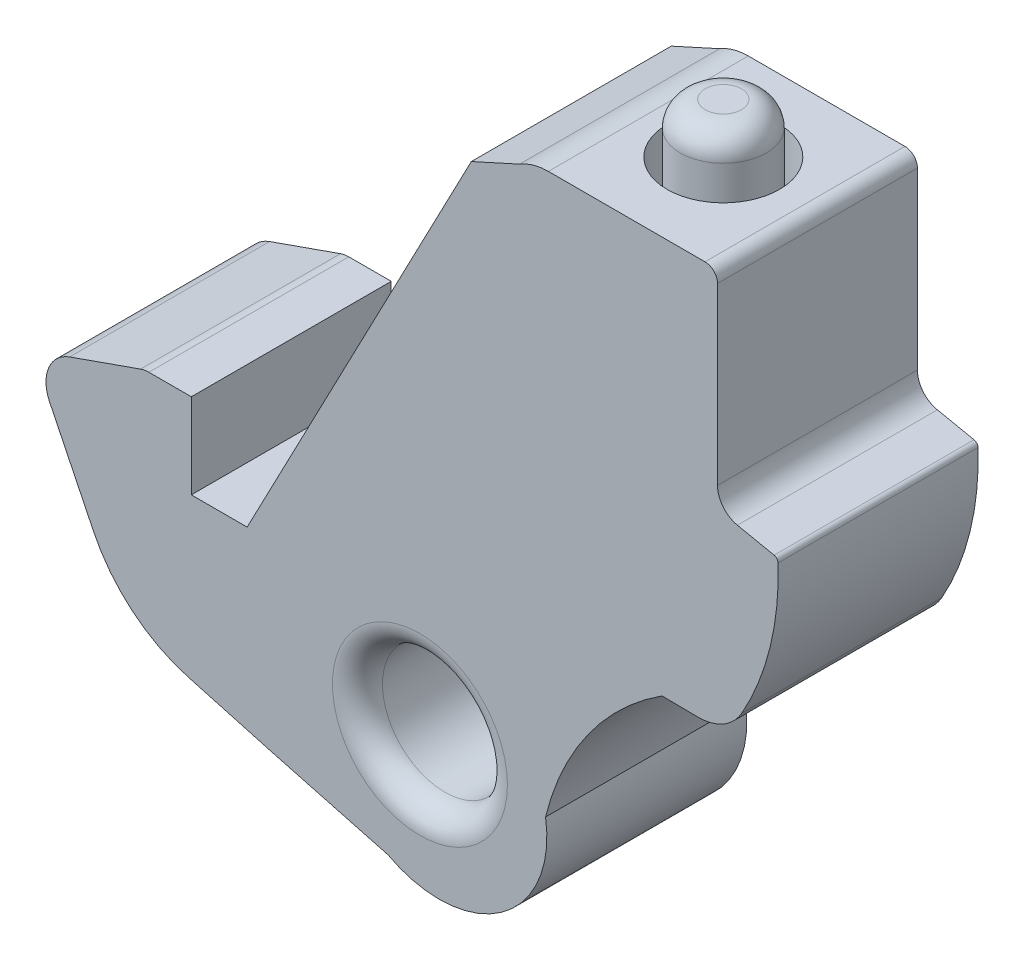
SolidWorks part; units mm, degrees
ref_plane "정면" through (0, 0, 0) normal (0, 0, 1) x (1, 0, 0)
ref_plane "윗면" through (0, 0, 0) normal (0, 1, 0) x (1, 0, 0)
ref_plane "우측면" through (0, 0, 0) normal (1, 0, 0) x (0, 0, -1)
sketch "스케치2" plane through (0, 0, 0) normal (0, 0, 1) x (1, 0, 0)
  line L0 (8.3179, 16.2244) -> (13.7243, 16.2244)
  line L1 (12.8641, 0.3222) -> (14.2933, 0.3052)
  line L4 (1.8992, -10.6672) -> (-2.7139, -9.4391)
  line L5 (-9.8819, -5.3519) -> (-11.6419, -1.7398)
  line L6 (-3.7359, -2.1289) -> (-5.9695, -2.1289)
  line L8 (13.7243, 16.2244) -> (15.0847, 16.2244)
  line L9 (-7.9998, 1.2144) -> (-10.839, 0.2157)
  line L10 (-3.7359, -2.1289) -> (5.2348, 15.0243)
  line L11 (15.0847, 16.2244) -> (15.0847, 8.7244)
  line L12 (-6.0867, -8.5069) -> (-2.7139, -9.4391)
  line L13 (-5.9695, -2.1289) -> (-5.9695, 1.2711)
  line L14 (15.8824, 7.745) -> (17.3492, 7.4421)
  line L15 (-5.9695, 1.2711) -> (-7.668, 1.2711)
  line L16 (5.2348, 15.0243) -> (7.1669, 15.9006)
  circle A0 centre (3.179, -5.8595) radius 2.5
  arc A1 (17.5086, 7.2531) -> (16.059, 1.3221) centre (6.2352, 6.8658) cw
  arc A2 (12.8641, 0.3222) -> (8.2055, -6.2043) centre (18.6948, -8.7657) ccw
  arc A3 (-9.8819, -5.3519) -> (-6.0867, -8.5069) centre (-4.4881, -2.7237) ccw
  arc A4 (16.059, 1.3221) -> (14.2933, 0.3052) centre (14.3172, 2.305) cw
  arc A5 (8.2055, -6.2043) -> (1.8992, -10.6672) centre (3.9468, -6.8736) cw
  arc A6 (-10.839, 0.2157) -> (-11.6419, -1.7398) centre (-10.3693, -1.1197) ccw
  arc A7 (17.3492, 7.4421) -> (17.5086, 7.2531) centre (17.3087, 7.2462) cw
  arc A8 (15.0847, 8.7244) -> (15.8824, 7.745) centre (16.0847, 8.7244) ccw
  arc A10 (8.3179, 16.2244) -> (7.1669, 15.9006) centre (8.3179, 14.0167) ccw
  arc A11 (-7.9998, 1.2144) -> (-7.668, 1.2711) centre (-7.668, 0.2711) cw
  dimension "D1" = 5
  dimension "D2" = 0.2
  dimension "D3" = 3.4
  dimension "D4" = 6
  dimension "D5" = 2
  dimension "D6" = 1
  dimension "D7" = 7.5
  dimension "D8" = 1
extrude "보스-돌출1" add sketch "스케치2" along normal blind 8
sketch "스케치9" plane through (0, 16.2244, 0) normal (0, 1, 0) x (1, 0, 0)
  line L1 (11.3179, -4) -> (8.3179, -4) construction
  line L2 (8.3179, -8) -> (8.3179, 0) construction
  circle A0 centre (11.3179, -4) radius 2.25
  dimension "D1" = 4.5
  dimension "D2" = 3
extrude "컷-돌출6" cut sketch "스케치9" against normal blind 2
sketch "스케치10" plane through (0, 14.2244, 0) normal (0, 1, 0) x (1, 0, 0)
  circle A0 centre (11.3179, -4) radius 1.725
  dimension "D1" = 3.45
extrude "보스-돌출3" add sketch "스케치10" along normal blind 4
fillet "필렛9" radius 1 1 edges at (11.3179, 18.2244, 5.725)
fillet "필렛6" radius 1 2 edges at (5.679, -5.8595, 8) (5.679, -5.8595, 0)
sketch "스케치8" plane through (0, 16.2244, 0) normal (0, 1, 0) x (1, 0, 0)
  line L4 (15.0847, 0) -> (8.3179, 0)
  line L5 (15.0847, 0) -> (8.3179, 0)
  line L6 (8.3179, 0) -> (8.3179, -8)
  line L7 (8.3179, 0) -> (8.3179, -8)
  line L8 (8.3179, -8) -> (15.0847, -8)
  line L9 (8.3179, -8) -> (15.0847, -8)
  line L10 (15.0847, -8) -> (15.0847, 0)
  line L11 (15.0847, -8) -> (15.0847, 0)
  dimension "D1" = 0
fillet "필렛11" radius 0.5 1 edges at (15.0847, 16.2244, 4)
